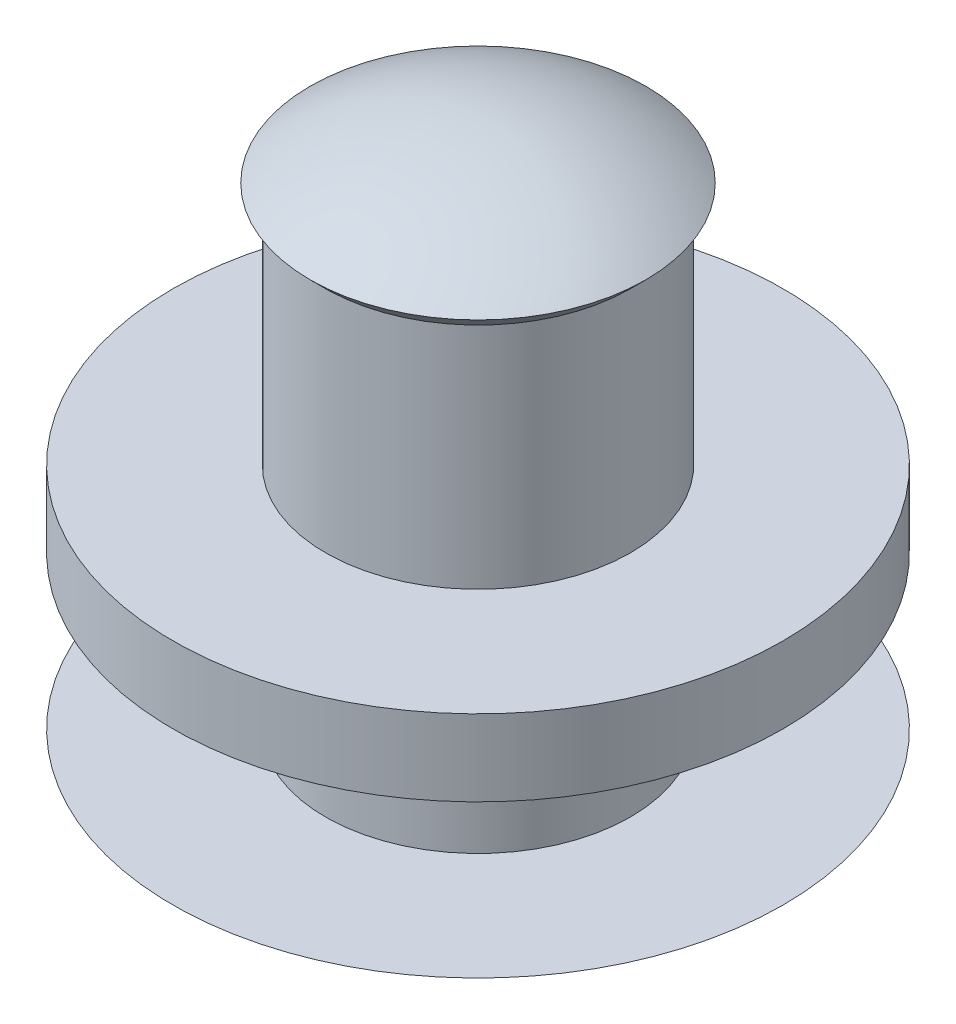
SolidWorks part; units mm, degrees
material "Stainless Steel (ferritic)"
ref_plane "Front Plane" through (0, 0, 0) normal (0, 0, 1) x (1, 0, 0)
ref_plane "Top Plane" through (0, 0, 0) normal (0, 1, 0) x (1, 0, 0)
ref_plane "Right Plane" through (0, 0, 0) normal (1, 0, 0) x (0, 0, -1)
sketch "Sketch2" plane through (0, 0, 0) normal (0, 0, 1) x (1, 0, 0)
  line L0 (0, 0) -> (0, 1) construction
  line L1 (0, -0.3) -> (0, 3.4416)
  line L2 (0, 0) -> (0, -0.3) construction
  line L3 (0, -0.3) -> (-0.4757, -0.3) construction
  line L6 (2, 0) -> (1, 0)
  line L7 (1, 0) -> (1, 1)
  line L9 (0, 1) -> (0, 1.5) construction
  line L10 (1, 1) -> (2, 1)
  line L11 (2, 1) -> (2, 1.5)
  line L12 (2, 1.5) -> (1, 1.5)
  line L15 (0, 1.5) -> (0, 3) construction
  line L17 (1, 1.5) -> (1, 3)
  line L19 (0, 3) -> (0, 3.1) construction
  line L21 (1, 3) -> (1.1, 3.1)
  line L23 (0, 0) -> (2, 0) construction
  line L24 (0, 3.1) -> (1.1, 3.1) construction
  line L25 (0, 3) -> (1, 3) construction
  arc A3 (2, 0) -> (0, -0.3) centre (0, 6.5167) cw
  arc A4 (1.1, 3.1) -> (0, 3.4416) centre (0, 1.5) ccw
  point P6 (0, 0)
  point P12 (0, 0)
  point P28 (0, 3.1)
  dimension "D3" = 0.3
  dimension "D4" = 2
  dimension "D1" = 1
  dimension "D2" = 1.5
  dimension "D5" = 0.5
  dimension "D6" = 1
  dimension "D7" = 0.1
  dimension "D8" = 135
revolve "Revolve7" add sketch "Sketch2" angle 360 about L1
